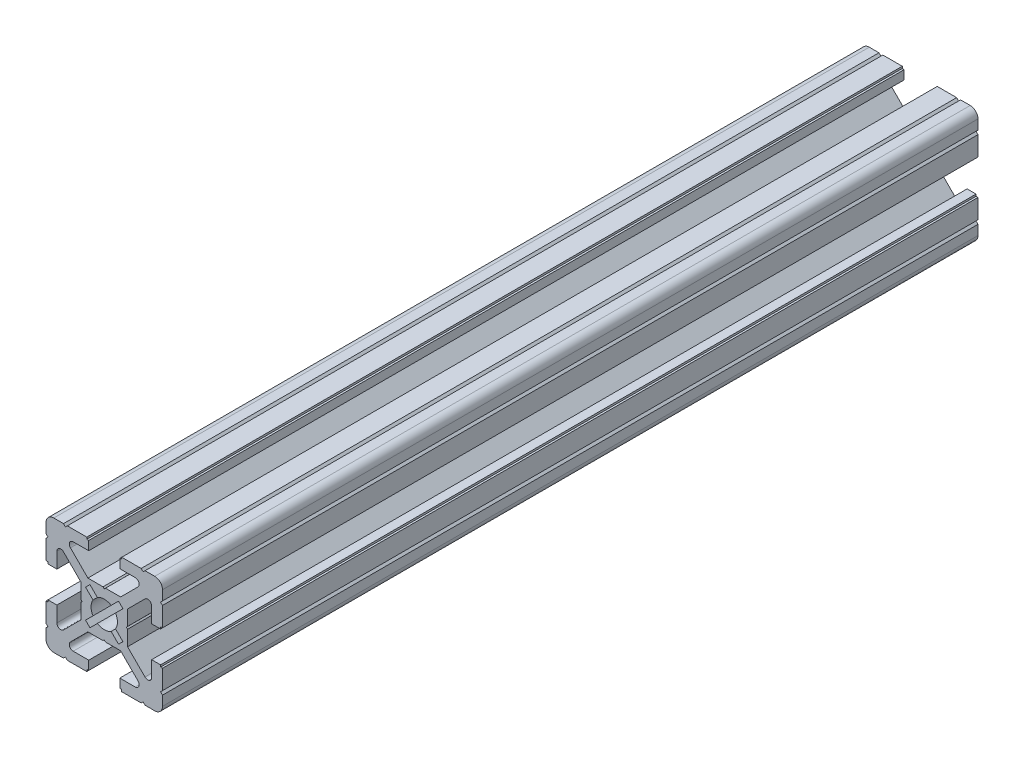
SolidWorks part; units mm, degrees
material "1060 Alloy"
ref_plane "Front" through (0, 0, 0) normal (0, 0, 1) x (1, 0, 0)
ref_plane "Top" through (0, 0, 0) normal (0, 1, 0) x (1, 0, 0)
ref_plane "Right" through (0, 0, 0) normal (1, 0, 0) x (0, 0, -1)
sketch "Sketch1" plane through (0, 0, 0) normal (0, 0, 1) x (1, 0, 0)
  line L0 (-2.9023, 1.771) -> (-4.8083, 3.677)
  line L1 (-4.8083, 3.677) -> (-3.677, 4.8083)
  line L2 (-3.677, 4.8083) -> (-1.771, 2.9023)
  line L3 (1.771, 2.9023) -> (3.677, 4.8083)
  line L4 (3.677, 4.8083) -> (4.8083, 3.677)
  line L5 (4.8083, 3.677) -> (2.9023, 1.771)
  line L6 (2.9023, -1.771) -> (4.8083, -3.677)
  line L7 (4.8083, -3.677) -> (3.677, -4.8083)
  line L8 (3.677, -4.8083) -> (1.771, -2.9023)
  line L9 (-1.771, -2.9023) -> (-3.677, -4.8083)
  line L10 (-3.677, -4.8083) -> (-4.8083, -3.677)
  line L11 (-4.8083, -3.677) -> (-2.9023, -1.771)
  line L12 (13, 15) -> (10.5, 15)
  line L13 (10.5, 15) -> (10, 14.5)
  line L14 (10, 14.5) -> (9.5, 15)
  line L15 (9.5, 15) -> (4.5, 15)
  line L16 (4.5, 15) -> (4.5, 14.5)
  line L17 (4.5, 14.5) -> (4, 14.5)
  line L18 (4, 14.5) -> (4, 12.2)
  line L19 (4, 12.2) -> (8, 12.2)
  line L20 (8.7071, 10.4929) -> (4.2142, 6)
  line L21 (4.2142, 6) -> (0.3125, 6)
  line L22 (0.3125, 6) -> (0, 5.7)
  line L23 (0, 5.7) -> (-0.3125, 6)
  line L24 (-0.3125, 6) -> (-4.2142, 6)
  line L25 (-4.2142, 6) -> (-8.7071, 10.4929)
  line L26 (-8, 12.2) -> (-4, 12.2)
  line L27 (-4, 12.2) -> (-4, 14.5)
  line L28 (-4, 14.5) -> (-4.5, 14.5)
  line L29 (-4.5, 14.5) -> (-4.5, 15)
  line L30 (-4.5, 15) -> (-9.5, 15)
  line L31 (-9.5, 15) -> (-10, 14.5)
  line L32 (-10, 14.5) -> (-10.5, 15)
  line L33 (-10.5, 15) -> (-13, 15)
  line L34 (-15, 13) -> (-15, 10.5)
  line L35 (-15, 10.5) -> (-14.5, 10)
  line L36 (-14.5, 10) -> (-15, 9.5)
  line L37 (-15, 9.5) -> (-15, 4.5)
  line L38 (-15, 4.5) -> (-14.5, 4.5)
  line L39 (-14.5, 4.5) -> (-14.5, 4)
  line L40 (-14.5, 4) -> (-12.2, 4)
  line L41 (-12.2, 4) -> (-12.2, 8)
  line L42 (-10.4929, 8.7071) -> (-6, 4.2142)
  line L43 (-6, 4.2142) -> (-6, 0.3125)
  line L44 (-6, 0.3125) -> (-5.7, 0)
  line L45 (-5.7, 0) -> (-6, -0.3125)
  line L46 (-6, -0.3125) -> (-6, -4.2142)
  line L47 (-6, -4.2142) -> (-10.4929, -8.7071)
  line L48 (-12.2, -8) -> (-12.2, -4)
  line L49 (-12.2, -4) -> (-14.5, -4)
  line L50 (-14.5, -4) -> (-14.5, -4.5)
  line L51 (-14.5, -4.5) -> (-15, -4.5)
  line L52 (-15, -4.5) -> (-15, -9.5)
  line L53 (-15, -9.5) -> (-14.5, -10)
  line L54 (-14.5, -10) -> (-15, -10.5)
  line L55 (-15, -10.5) -> (-15, -13)
  line L56 (-13, -15) -> (-10.4899, -15)
  line L57 (-10.4899, -15) -> (-9.9899, -14.5)
  line L58 (-9.9899, -14.5) -> (-9.5, -15)
  line L59 (-9.5, -15) -> (-4.5, -15)
  line L60 (-4.5, -15) -> (-4.5, -14.5)
  line L61 (-4.5, -14.5) -> (-4, -14.5)
  line L62 (-4, -14.5) -> (-4, -12.2)
  line L63 (-4, -12.2) -> (-8, -12.2)
  line L64 (-8.7071, -10.4929) -> (-4.2142, -6)
  line L65 (-4.2142, -6) -> (-0.3125, -6)
  line L66 (-0.3125, -6) -> (0, -5.7)
  line L67 (0, -5.7) -> (0.3125, -6)
  line L68 (0.3125, -6) -> (4.2142, -6)
  line L69 (4.2142, -6) -> (8.7071, -10.4929)
  line L70 (8, -12.2) -> (4, -12.2)
  line L71 (4, -12.2) -> (4, -14.5)
  line L72 (4, -14.5) -> (4.5, -14.5)
  line L73 (4.5, -14.5) -> (4.5, -15)
  line L74 (4.5, -15) -> (9.5, -15)
  line L75 (9.5, -15) -> (10, -14.5)
  line L76 (10, -14.5) -> (10.5, -15)
  line L77 (10.5, -15) -> (13, -15)
  line L78 (15, -13) -> (15, -10.5)
  line L79 (15, -10.5) -> (14.5, -10)
  line L80 (14.5, -10) -> (15, -9.5)
  line L81 (15, -9.5) -> (15, -4.5)
  line L82 (15, -4.5) -> (14.5, -4.5)
  line L83 (14.5, -4.5) -> (14.5, -4)
  line L84 (14.5, -4) -> (12.2, -4)
  line L85 (12.2, -4) -> (12.2, -8)
  line L86 (10.4929, -8.7071) -> (6, -4.2142)
  line L87 (6, -4.2142) -> (6, -0.3125)
  line L88 (6, -0.3125) -> (5.7, 0)
  line L89 (5.7, 0) -> (6, 0.3125)
  line L90 (6, 0.3125) -> (6, 4.2142)
  line L91 (6, 4.2142) -> (10.4929, 8.7071)
  line L92 (12.2, 8) -> (12.2, 4)
  line L93 (12.2, 4) -> (14.5, 4)
  line L94 (14.5, 4) -> (14.5, 4.5)
  line L95 (14.5, 4.5) -> (15, 4.5)
  line L96 (15, 4.5) -> (15, 9.5)
  line L97 (15, 9.5) -> (14.5, 10)
  line L98 (14.5, 10) -> (15, 10.5)
  line L99 (15, 10.5) -> (15, 13)
  arc A0 (-1.771, 2.9023) -> (1.771, 2.9023) centre (0, 0) cw
  arc A1 (2.9023, 1.771) -> (2.9023, -1.771) centre (0, 0) cw
  arc A2 (1.771, -2.9023) -> (-1.771, -2.9023) centre (0, 0) cw
  arc A3 (-2.9023, -1.771) -> (-2.9023, 1.771) centre (0, 0) cw
  arc A4 (8, 12.2) -> (8.7071, 10.4929) centre (8, 11.2) cw
  arc A5 (-8.7071, 10.4929) -> (-8, 12.2) centre (-8, 11.2) cw
  arc A6 (-13, 15) -> (-15, 13) centre (-13, 13) ccw
  arc A7 (-12.2, 8) -> (-10.4929, 8.7071) centre (-11.2, 8) cw
  arc A8 (-10.4929, -8.7071) -> (-12.2, -8) centre (-11.2, -8) cw
  arc A9 (-15, -13) -> (-13, -15) centre (-13, -13) ccw
  arc A10 (-8, -12.2) -> (-8.7071, -10.4929) centre (-8, -11.2) cw
  arc A11 (8.7071, -10.4929) -> (8, -12.2) centre (8, -11.2) cw
  arc A12 (13, -15) -> (15, -13) centre (13, -13) ccw
  arc A13 (12.2, -8) -> (10.4929, -8.7071) centre (11.2, -8) cw
  arc A14 (10.4929, 8.7071) -> (12.2, 8) centre (11.2, 8) cw
  arc A15 (15, 13) -> (13, 15) centre (13, 13) ccw
  dimension "D3" = 3.4
  dimension "D7" = 2
  dimension "D1" = 30
  dimension "D2" = 30
  dimension "D4" = 9
  dimension "D5" = 9
  dimension "D6" = 8
  dimension "D8" = 2.8
extrude "Boss-Extrude1" add sketch "Sketch1" along normal blind 210
